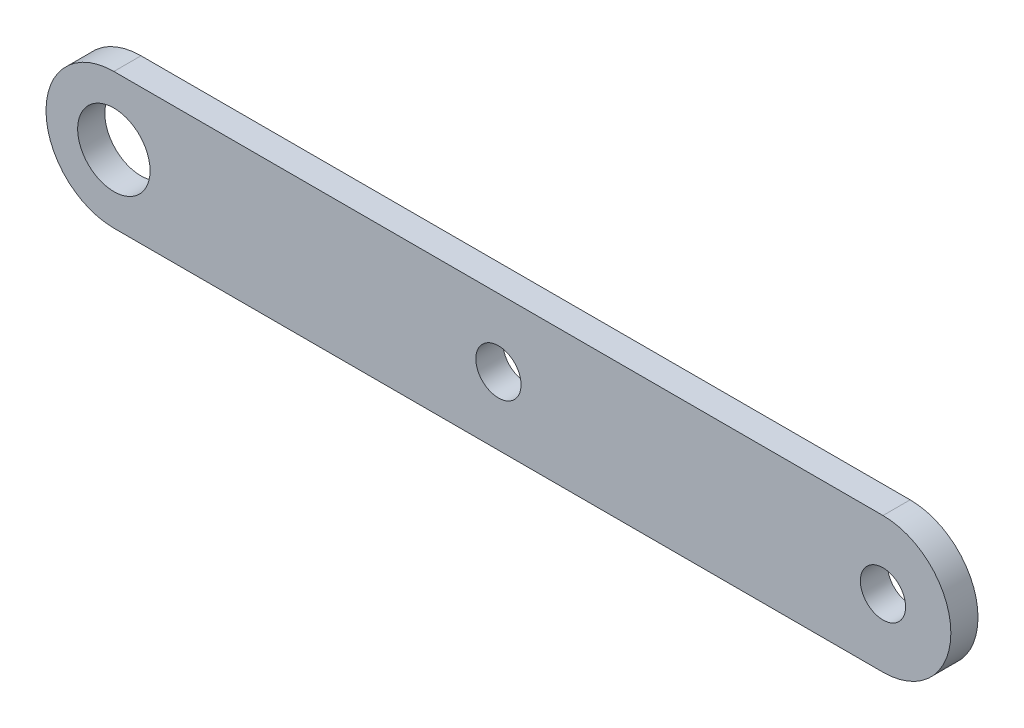
SolidWorks part; units mm, degrees
ref_plane "前视基准面" through (0, 0, 0) normal (0, 0, 1) x (1, 0, 0)
ref_plane "上视基准面" through (0, 0, 0) normal (0, 1, 0) x (1, 0, 0)
ref_plane "右视基准面" through (0, 0, 0) normal (1, 0, 0) x (0, 0, -1)
sketch "草图1" plane through (0, 0, 0) normal (0, 0, 1) x (1, 0, 0)
  line L0 (-42.5, 7.5) -> (-42.5, -7.5) construction
  line L1 (-42.5, -7.5) -> (42.5, -7.5)
  line L3 (-42.5, 7.5) -> (42.5, 7.5)
  line L5 (-42.5, -7.5) -> (42.5, 7.5) construction
  line L6 (-42.5, 7.5) -> (42.5, -7.5) construction
  arc A0 (-42.5, 7.5) -> (-42.5, -7.5) centre (-42.5, 0) ccw
  arc A1 (42.5, -7.5) -> (42.5, 7.5) centre (42.5, 0) ccw
  circle A2 centre (-42.5, 0) radius 4
  circle A3 centre (42.5, 0) radius 2.5
  circle A4 centre (0, 0) radius 2.5
  point P0 (0, 0)
  dimension "D3" = 8
  dimension "D4" = 5
  dimension "D5" = 5
  dimension "D1" = 15
  dimension "D2" = 85
extrude "凸台-拉伸1" add sketch "草图1" along normal blind 3
